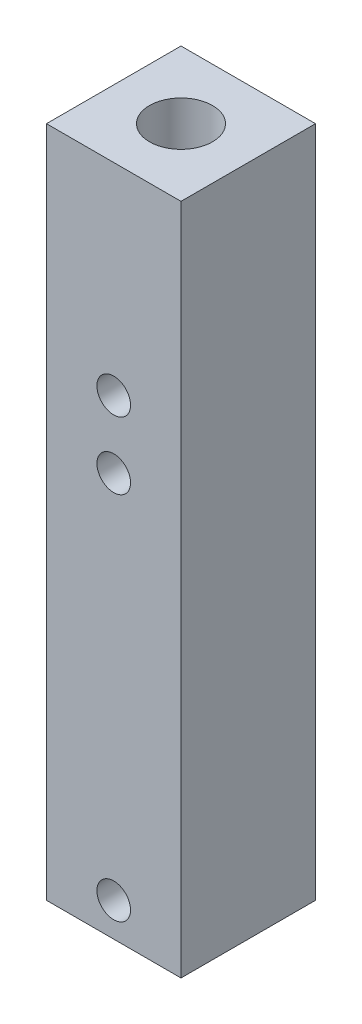
SolidWorks part; units mm, degrees
ref_plane "Front Plane" through (0, 0, 0) normal (0, 0, 1) x (1, 0, 0)
ref_plane "Top Plane" through (0, 0, 0) normal (0, 1, 0) x (1, 0, 0)
ref_plane "Right Plane" through (0, 0, 0) normal (1, 0, 0) x (0, 0, -1)
sketch "Sketch1" plane through (0, 0, 0) normal (0, 1, 0) x (1, 0, 0)
  line L1 (-10, 10) -> (10, 10)
  line L2 (-10, 10) -> (-10, -10)
  line L3 (-10, -10) -> (10, -10)
  line L4 (10, 10) -> (10, -10)
  line L5 (-10, 10) -> (10, -10) construction
  line L6 (-10, -10) -> (10, 10) construction
  circle A0 centre (0, 0) radius 4.6831
  point P0 (0, 0)
  dimension "D1" = 20
  dimension "D2" = 20
extrude "Boss-Extrude1" add sketch "Sketch1" along normal blind 100
sketch "Sketch2" plane through (0, 0, 10) normal (0, 0, 1) x (1, 0, 0)
  line L0 (-10, 0) -> (10, 0) construction
  circle A0 centre (0, 5) radius 2.5
  dimension "D1" = 5
  dimension "D2" = 5
extrude "Cut-Extrude1" cut sketch "Sketch2" against normal blind 100
sketch "Sketch3" plane through (0, 0, 10) normal (0, 0, 1) x (1, 0, 0)
  line L0 (0, -1000) -> (0, 49000) construction
  line L1 (-10, 0) -> (10, 0) construction
  circle A0 centre (0, 60) radius 2.5
  circle A1 centre (0, 70) radius 2.5
  dimension "D1" = 60
  dimension "D2" = 5
  dimension "D3" = 5
  dimension "D4" = 10
extrude "Cut-Extrude2" cut sketch "Sketch3" against normal through all
